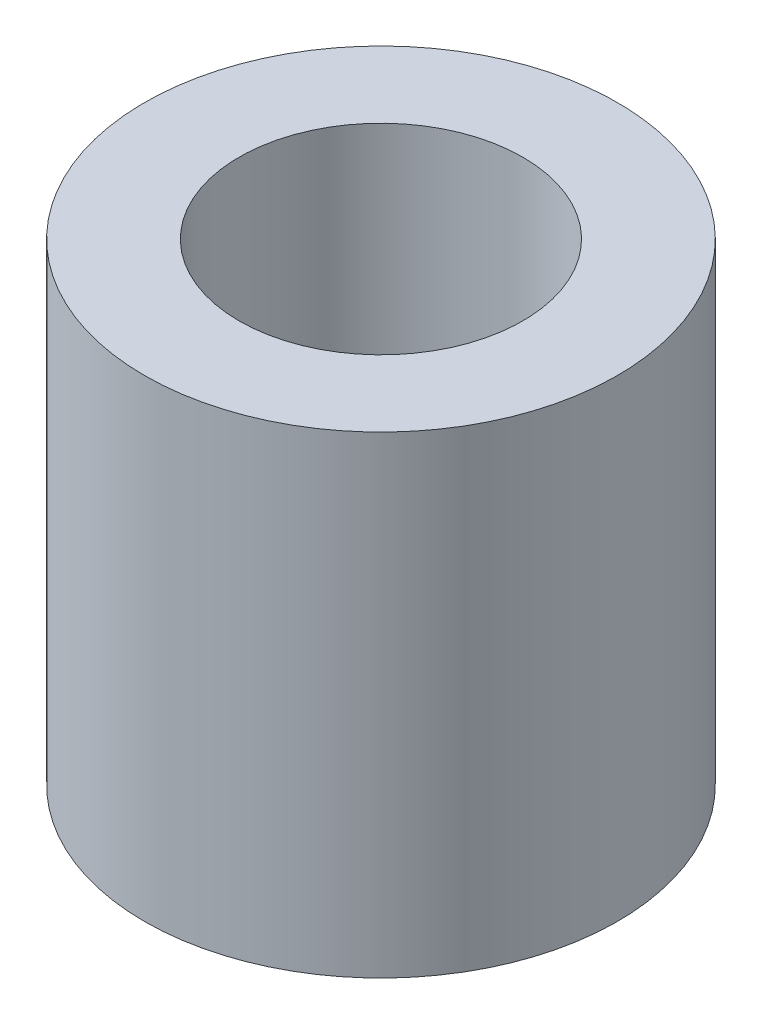
SolidWorks part; units mm, degrees
ref_plane "Plan de face" through (0, 0, 0) normal (0, 0, 1) x (1, 0, 0)
ref_plane "Plan de dessus" through (0, 0, 0) normal (0, 1, 0) x (1, 0, 0)
ref_plane "Plan de droite" through (0, 0, 0) normal (1, 0, 0) x (0, 0, -1)
sketch "Esquisse1" plane through (0, 0, 0) normal (0, 1, 0) x (1, 0, 0)
  circle A0 centre (0, 0) radius 1.5
  circle A1 centre (0, 0) radius 2.5
  dimension "D1" = 5
  dimension "D2" = 3
extrude "Extrusion1" add sketch "Esquisse1" along normal mid plane 5
